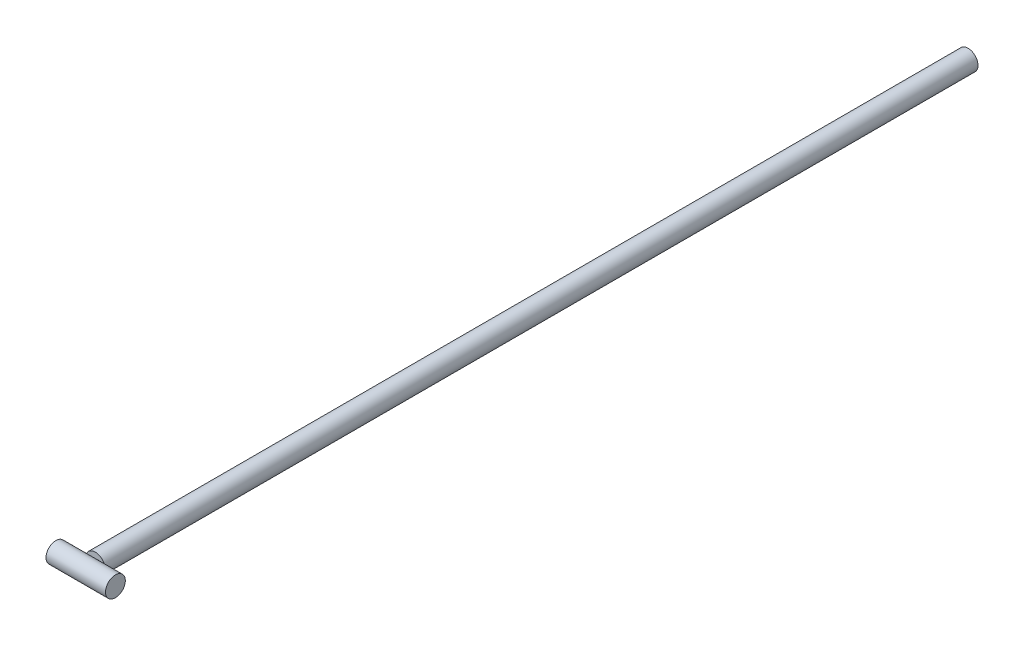
SolidWorks part; units mm, degrees
ref_plane "前视基准面" through (0, 0, 0) normal (0, 0, 1) x (1, 0, 0)
ref_plane "上视基准面" through (0, 0, 0) normal (0, 1, 0) x (1, 0, 0)
ref_plane "右视基准面" through (0, 0, 0) normal (1, 0, 0) x (0, 0, -1)
sketch "草图1" plane through (0, 0, 0) normal (0, 0, 1) x (1, 0, 0)
  circle A0 centre (0, 0) radius 2.5
  dimension "D1" = 5
extrude "凸台-拉伸1" add sketch "草图1" along normal mid plane 220
sketch "草图2" plane through (0, 0, 0) normal (1, 0, 0) x (0, 0, -1)
  circle A0 centre (-112.4405, 0) radius 2.5
  point P0 (-112.4405, 0.4047)
extrude "凸台-拉伸2" add sketch "草图2" along normal blind 7.5
mirror "镜向1" about plane through (0, 0, 0) normal (1, 0, 0) of "凸台-拉伸2"
